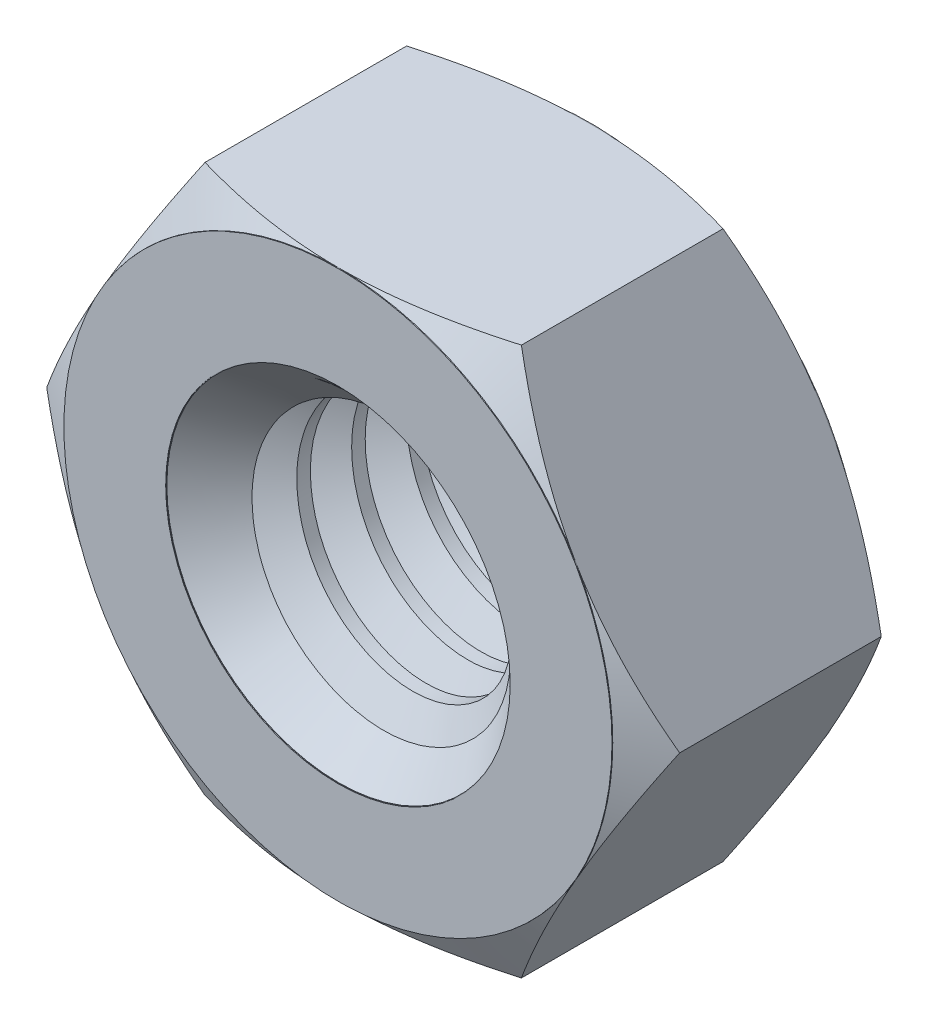
SolidWorks part; units mm, degrees
ref_plane "Front" through (0, 0, 0) normal (0, 0, 1) x (1, 0, 0)
ref_plane "Top" through (0, 0, 0) normal (0, 1, 0) x (1, 0, 0)
ref_plane "Right" through (0, 0, 0) normal (1, 0, 0) x (0, 0, -1)
sketch "Çizim1" plane through (0, 0, 0) normal (0, 0, 1) x (1, 0, 0)
  line L1 (4.0415, 0) -> (2.0207, 3.5)
  line L2 (2.0207, 3.5) -> (-2.0207, 3.5)
  line L3 (-2.0207, 3.5) -> (-4.0415, 0)
  line L4 (-4.0415, 0) -> (-2.0207, -3.5)
  line L5 (-2.0207, -3.5) -> (2.0207, -3.5)
  line L6 (2.0207, -3.5) -> (4.0415, 0)
  circle A0 centre (0, 0) radius 3.5 construction
  dimension "D1" = 7
extrude "Yükseklik-Ekstrüzyon1" add sketch "Çizim1" along normal blind 3.2
sketch "Çizim2" plane through (0, 0, 3.2) normal (0, 0, 1) x (1, 0, 0)
  circle A0 centre (0, 0) radius 3.5
extrude "Kes-Ekstrüzyon1" cut sketch "Çizim2" against normal blind 3.2 draft 60 flip side to cut
sketch "Çizim3" plane through (0, 0, 0) normal (0, 0, -1) x (-1, 0, 0)
  circle A0 centre (0, 0) radius 3.5
extrude "Kes-Ekstrüzyon2" cut sketch "Çizim3" against normal blind 3.2 draft 60 flip side to cut
sketch "Çizim5" plane through (0, 0, 0) normal (0, 0, -1) x (-1, 0, 0)
  circle A0 centre (0, 0) radius 1.545
  dimension "D1" = 3.09
extrude "Kes-Ekstrüzyon3" cut sketch "Çizim5" against normal blind 3.2
chamfer "Pah1" distance 0.65 angle 45 2 edges at (-1.545, 0, 3.2) (-1.545, 0, 0)
sketch "Çizim6" plane through (0, 0, 0) normal (0, 0, -1) x (-1, 0, 0)
  circle A0 centre (0, 0) radius 1.545
curve "Helis/Spiral1" pitch 0.7 height 4 turns 5.7143
ref_plane "Düzlem1" through (-0.3438, -1.5063, 4) normal (0.9724, -0.2219, 0.0719) x (0.0701, -0.016, -0.9974)
sketch "Çizim7" plane through (-0.3438, -1.5063, 4) normal (0.9724, -0.2219, 0.0719) x (0.0701, -0.016, -0.9974)
  line L0 (0.3473, 0.1465) -> (-0.3473, 0.1465)
  line L1 (0, -0.455) -> (0.3473, 0.1465)
  line L3 (-0.3473, 0.1465) -> (0, -0.455)
  line L5 (0.394, 0.2275) -> (0, 0.2275) [skipped]
  circle A0 centre (0, 0) radius 0.2275 construction
  dimension "D1" = 0.455
sweep "Kes-Süpür1" cut profiles "Çizim7" path "Helis/Spiral1"
sketch "Sketch1" plane through (0, 0, 0) normal (0, 0, 1) x (1, 0, 0)
  circle A0 centre (0, 0) radius 2.2
  circle A1 centre (0, 0) radius 3.5
extrude "Boss-Extrude1" add sketch "Sketch1" along normal blind 3.21 and the other way blind 0.01
